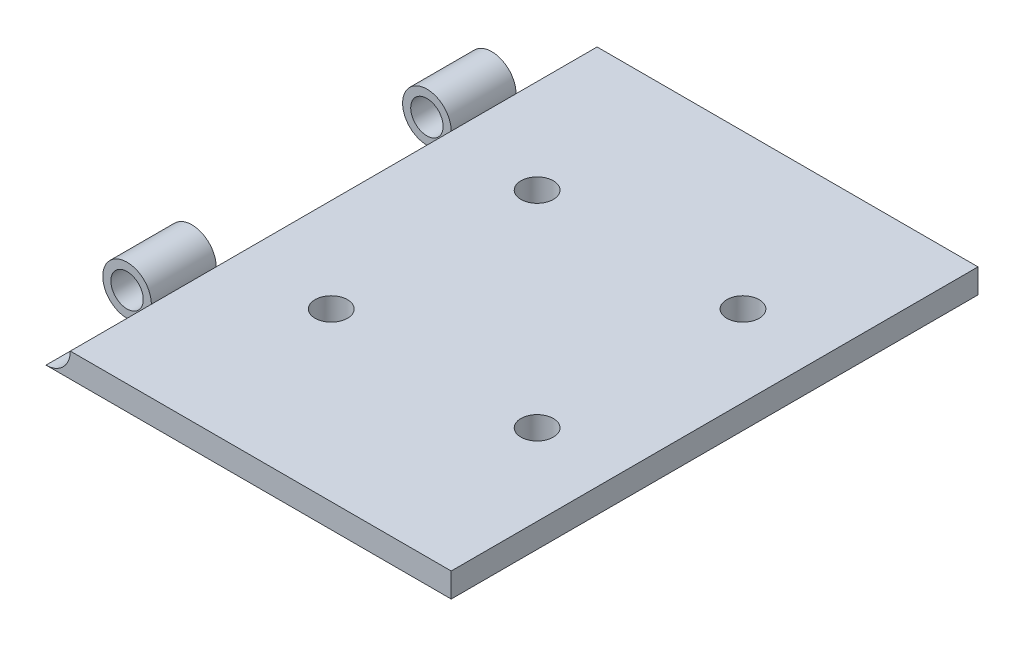
SolidWorks part; units mm, degrees
ref_plane "Front Plane" through (0, 0, 0) normal (0, 0, 1) x (1, 0, 0)
ref_plane "Top Plane" through (0, 0, 0) normal (0, 1, 0) x (1, 0, 0)
ref_plane "Right Plane" through (0, 0, 0) normal (1, 0, 0) x (0, 0, -1)
sketch "Sketch1" plane through (0, 0, 0) normal (0, 1, 0) x (1, 0, 0)
  line L1 (-25, -32.5) -> (25, -32.5)
  line L2 (-25, -32.5) -> (-25, 32.5)
  line L3 (-25, 32.5) -> (25, 32.5)
  line L4 (25, -32.5) -> (25, 32.5)
  line L5 (-25, -32.5) -> (25, 32.5) construction
  line L6 (-25, 32.5) -> (25, -32.5) construction
  point P0 (0, 0)
  dimension "D1" = 65
  dimension "D2" = 50
extrude "Boss-Extrude1" add sketch "Sketch1" along normal blind 3
ref_plane "Plane1" through (0, 0, 22.5) normal (0, 0, 1) x (1, 0, 0)
sketch "Sketch4" plane through (0, 0, 32.5) normal (0, 0, 1) x (1, 0, 0)
  circle A0 centre (-25, 3) radius 3
extrude "Cut-Extrude1" cut sketch "Sketch4" against normal blind 70
sketch "Sketch5" plane through (0, 0, 22.5) normal (0, 0, 1) x (1, 0, 0)
  circle A0 centre (-25, 3) radius 3
extrude "Boss-Extrude3" add sketch "Sketch5" against normal blind 8 separate body
ref_plane "Plane2" through (0, 0, -22.5) normal (0, 0, -1) x (-1, 0, 0)
sketch "Sketch6" plane through (0, 0, -22.5) normal (0, 0, -1) x (-1, 0, 0)
  circle A0 centre (25, 3) radius 3
extrude "Boss-Extrude4" add sketch "Sketch6" against normal blind 8
sketch "Sketch7" plane through (0, 0, 22.5) normal (0, 0, 1) x (1, 0, 0)
  circle A0 centre (-25, 3) radius 2
  dimension "D1" = 4
extrude "Cut-Extrude2" cut sketch "Sketch7" against normal blind 68
sketch "Sketch8" plane through (0, 3, 0) normal (0, 1, 0) x (1, 0, 0)
  line L0 (25, 32.5) -> (-22, 32.5) construction
  line L1 (25, -32.5) -> (25, 32.5) construction
  circle A0 centre (-10.4, 13.5) radius 2
  circle A1 centre (15, 13.5) radius 2
  circle A2 centre (15, -11.9) radius 2
  circle A3 centre (-10.4, -11.9) radius 2
  dimension "D1" = 4
  dimension "D4" = 19
  dimension "D5" = 10
  dimension "D2" = 2
  dimension "D3" = 2
extrude "Cut-Extrude3" cut sketch "Sketch8" against normal blind 38
